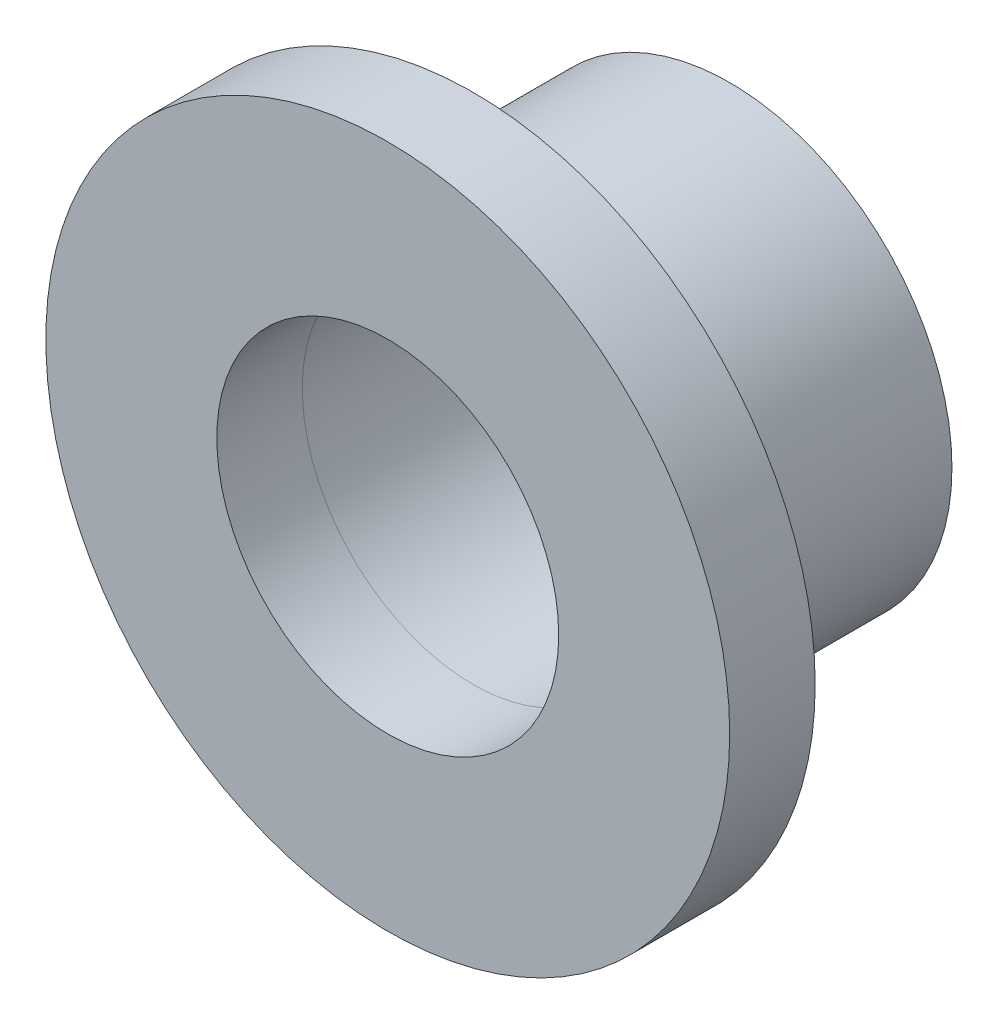
SolidWorks part; units mm, degrees
ref_plane "Front Plane" through (0, 0, 0) normal (0, 0, 1) x (1, 0, 0)
ref_plane "Top Plane" through (0, 0, 0) normal (0, 1, 0) x (1, 0, 0)
ref_plane "Right Plane" through (0, 0, 0) normal (1, 0, 0) x (0, 0, -1)
sketch "Sketch1" plane through (0, 0, 0) normal (0, 0, 1) x (1, 0, 0)
  circle A0 centre (0, 0) radius 10
  circle A1 centre (0, 0) radius 13
  dimension "D1" = 20
  dimension "D2" = 26
extrude "Boss-Extrude1" add sketch "Sketch1" along normal blind 15
sketch "Sketch2" plane through (0, 0, 15) normal (0, 0, 1) x (1, 0, 0)
  circle A0 centre (0, 0) radius 10
  circle A1 centre (0, 0) radius 20
  dimension "D1" = 40
  dimension "D2" = 20
extrude "Boss-Extrude2" add sketch "Sketch2" along normal blind 5 separate body
